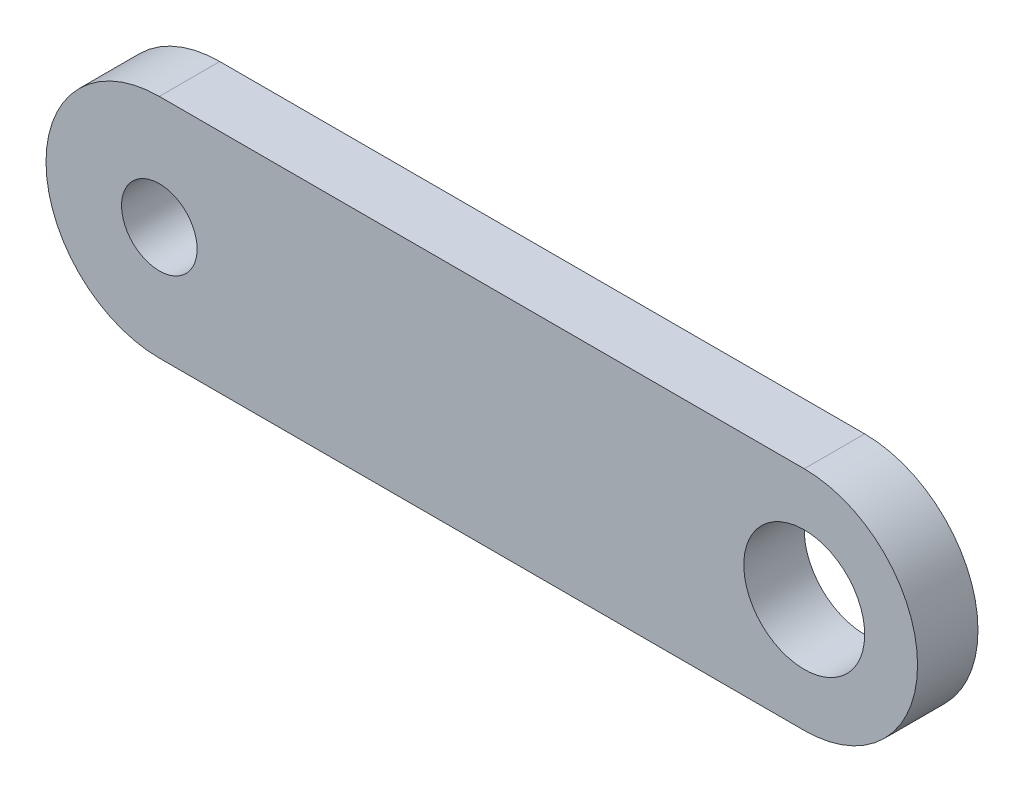
SolidWorks part; units mm, degrees
material "ABS"
ref_plane "Front Plane" through (0, 0, 0) normal (0, 0, 1) x (1, 0, 0)
ref_plane "Top Plane" through (0, 0, 0) normal (0, 1, 0) x (1, 0, 0)
ref_plane "Right Plane" through (0, 0, 0) normal (1, 0, 0) x (0, 0, -1)
sketch "Sketch1" plane through (0, 0, 0) normal (0, 0, 1) x (1, 0, 0)
  line L0 (0, 4.7625) -> (27.1018, 4.7625)
  line L1 (0, -4.7625) -> (27.1018, -4.7625)
  circle A0 centre (0, 0) radius 1.5875
  circle A1 centre (0, 0) radius 4.7625
  circle A2 centre (27.1018, 0) radius 2.54
  circle A3 centre (27.1018, 0) radius 4.7625
  dimension "D1" = 3.175
  dimension "D2" = 9.525
extrude "Boss-Extrude2" add sketch "Sketch1" along normal blind 2.54 contours A1 A0 | A3 A2 | A3 L0 A1 L1
